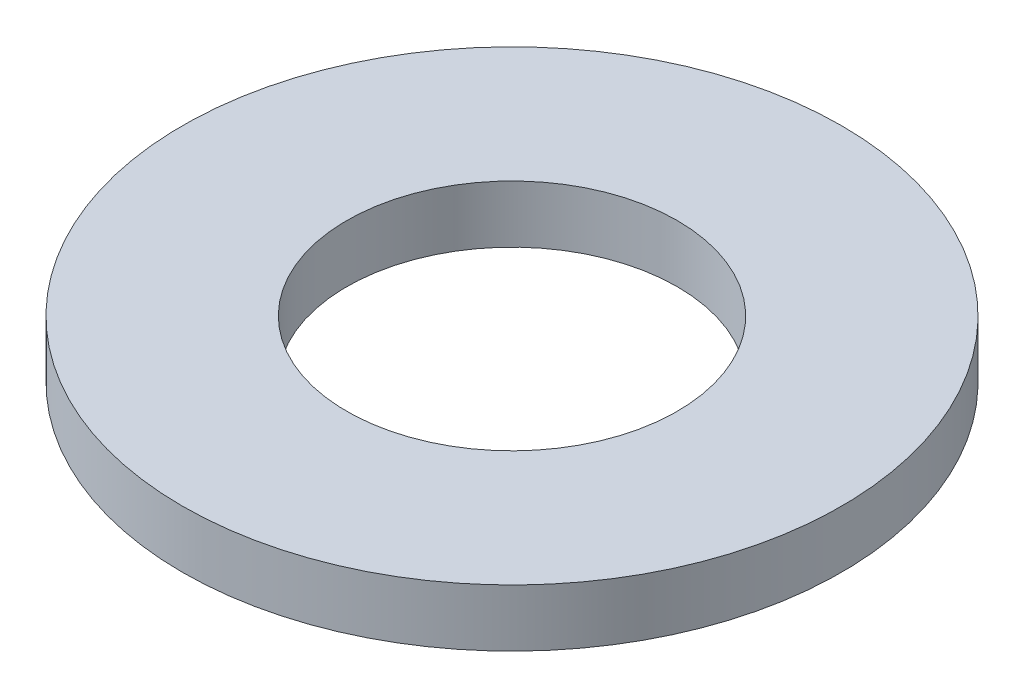
SolidWorks part; units mm, degrees
ref_plane "Front" through (0, 0, 0) normal (0, 0, 1) x (1, 0, 0)
ref_plane "Top" through (0, 0, 0) normal (0, 1, 0) x (1, 0, 0)
ref_plane "Right" through (0, 0, 0) normal (1, 0, 0) x (0, 0, -1)
sketch "Sketch1" plane through (0, 0, 0) normal (0, 1, 0) x (1, 0, 0)
  circle A0 centre (0, 0) radius 4.3942
  circle A1 centre (0, 0) radius 8.763
  dimension "D1" = 8.7884
  dimension "D2" = 17.526
extrude "Extrude1" add sketch "Sketch1" along normal blind 1.524
